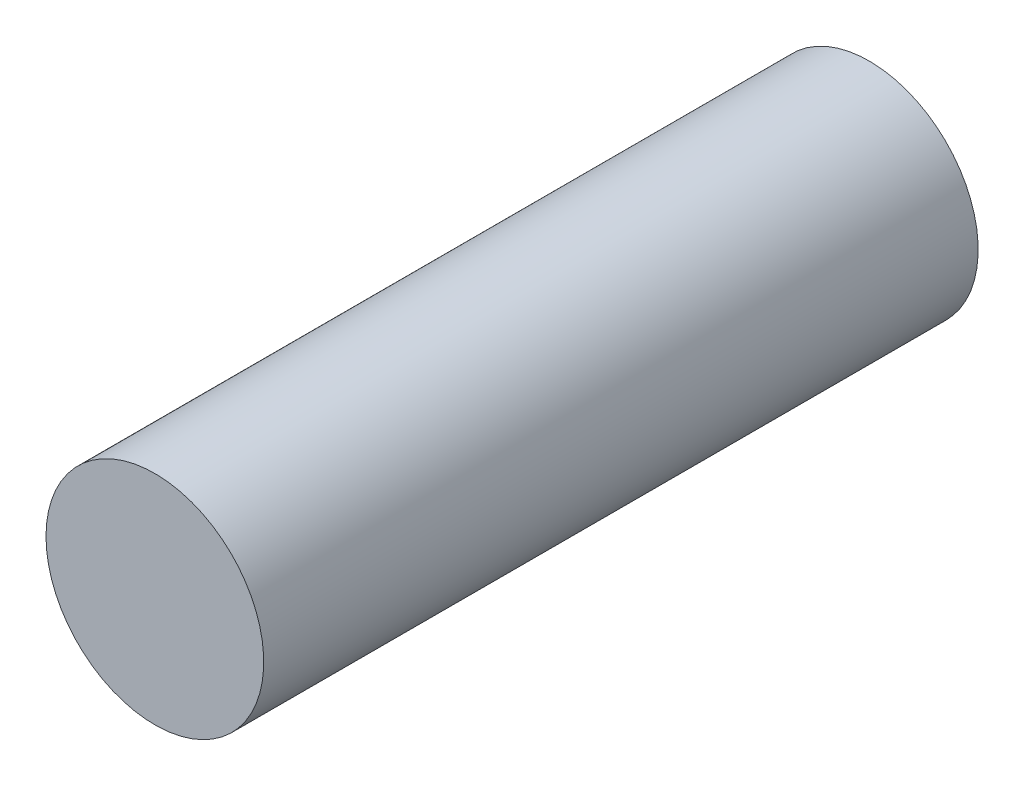
SolidWorks part; units mm, degrees
ref_plane "Front Plane" through (0, 0, 0) normal (0, 0, 1) x (1, 0, 0)
ref_plane "Top Plane" through (0, 0, 0) normal (0, 1, 0) x (1, 0, 0)
ref_plane "Right Plane" through (0, 0, 0) normal (1, 0, 0) x (0, 0, -1)
sketch "Sketch1" plane through (0, 0, 0) normal (0, 0, 1) x (1, 0, 0)
  circle A0 centre (0, 0) radius 3.2
  dimension "D1" = 6.4
extrude "Boss-Extrude1" add sketch "Sketch1" along normal blind 21
scale "缩放比例1" scale about centroid uniform scaling yes scale factor 2
